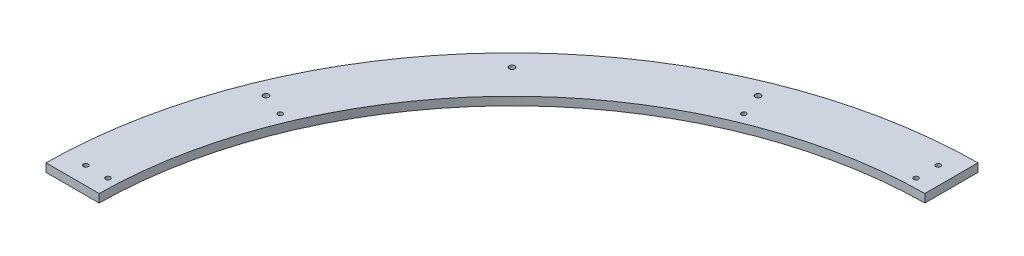
SolidWorks part; units mm, degrees
material "Pine"
ref_plane "Front Plane" through (0, 0, 0) normal (0, 0, 1) x (1, 0, 0)
ref_plane "Top Plane" through (0, 0, 0) normal (0, 1, 0) x (1, 0, 0)
ref_plane "Right Plane" through (0, 0, 0) normal (1, 0, 0) x (0, 0, -1)
sketch "Sketch1" plane through (0, 0, 0) normal (0, 1, 0) x (1, 0, 0)
  line L0 (-598.4875, 0) -> (-674.6875, 0)
  line L1 (598.4875, 0) -> (674.6875, 0)
  arc A0 (-598.4875, 0) -> (598.4875, 0) centre (0, 0) cw
  arc A1 (-674.6875, 0) -> (674.6875, 0) centre (0, 0) cw
  dimension "D2" = 598.4875
  dimension "D1" = 76.2
extrude "Boss-Extrude1" add sketch "Sketch1" along normal blind 11.9062
sketch "Sketch2" plane through (0, 11.9062, 0) normal (0, 1, 0) x (1, 0, 0)
  line L1 (-6.35, 598.4538) -> (6.35, 598.4538)
  line L2 (-6.35, 598.4538) -> (-6.35, 636.5875)
  line L3 (-6.35, 636.5875) -> (6.35, 636.5875)
  line L4 (6.35, 598.4538) -> (6.35, 636.5875)
  line L8 (598.4538, 6.35) -> (636.5875, 6.35)
  line L9 (0, 0) -> (0, 598.4538) construction
  line L14 (0, 674.6875) -> (0, 598.4875) construction
  line L15 (598.4538, 6.35) -> (598.4538, -6.35)
  line L16 (598.4538, -6.35) -> (636.5875, -6.35)
  line L17 (636.5875, 6.35) -> (636.5875, -6.35)
  line L18 (6.35, -598.4538) -> (6.35, -636.5875)
  line L19 (6.35, -598.4538) -> (-6.35, -598.4538)
  line L20 (-6.35, -598.4538) -> (-6.35, -636.5875)
  line L21 (6.35, -636.5875) -> (-6.35, -636.5875)
  line L22 (-598.4538, -6.35) -> (-636.5875, -6.35)
  line L23 (-598.4538, -6.35) -> (-598.4538, 6.35)
  line L24 (-598.4538, 6.35) -> (-636.5875, 6.35)
  line L25 (-636.5875, -6.35) -> (-636.5875, 6.35)
  line L26 (598.4875, 0) -> (674.6875, 0) construction
  arc A0 (598.4875, 0) -> (-598.4875, 0) centre (0, 0) ccw construction
  arc A1 (674.6875, 0) -> (-674.6875, 0) centre (0, 0) ccw construction
  point P7 (0, 598.4538)
  point P16 (0, 0)
  point P23 (0, 636.5875)
  point P33 (0, 0)
  dimension "D1" = 38.1
  dimension "D2" = 12.7
  dimension "D3" = 4
extrude "Cut-Extrude1" cut sketch "Sketch2" against normal through all
hole_wizard "1/4 Clearance Hole2" positions "Sketch6" profile "Sketch7" hole size "1/4" standard "ANSI Inch" end condition through all
sketch "Sketch6" plane through (0, 11.9062, 0) normal (0, 1, 0) x (1, 0, 0)
  line L0 (0, 636.5875) -> (0, 598.4875) construction
  line L1 (6.35, 636.5875) -> (-6.35, 636.5875) construction
  line L2 (-6.35, 636.5875) -> (-6.35, 598.4538) construction
  line L3 (-636.5875, 0) -> (-598.4875, 0) construction
  line L4 (-31.75, 642.9375) -> (-31.75, 611.1875) construction
  line L5 (-31.75, 611.1875) -> (-31.75, 598.4875) construction
  line L6 (-31.75, 598.4875) -> (0, 598.4875) construction
  line L8 (-598.4875, 0) -> (-598.4875, 31.75) construction
  line L9 (-598.4875, 31.75) -> (-611.1875, 31.75) construction
  line L10 (-611.1875, 31.75) -> (-642.9375, 31.75) construction
  line L11 (-598.4875, 0) -> (-552.9304, 229.0313) construction
  line L12 (-552.9304, 229.0313) -> (-423.1946, 423.1946) construction
  line L13 (-423.1946, 423.1946) -> (0, 0) construction
  line L15 (-552.9304, 229.0313) -> (-567.5969, 235.1064) construction
  arc A0 (-6.35, 598.4538) -> (-598.4538, 6.35) centre (0, 0) ccw construction
  point P0 (-31.75, 642.9375)
  point P2 (-31.75, 611.1875)
  point P39 (-611.1875, 31.75)
  point P42 (-642.9375, 31.75)
  point P62 (-567.5969, 235.1064)
  point P70 (-235.1064, 567.5969)
  dimension "D1" = 38.1
  dimension "D2" = 25.4
  dimension "D3" = 12.7
  dimension "D4" = 31.75
  dimension "D5" = 15.875
sketch "Sketch7" plane through (-31.75, 11.9062, -642.9375) normal (1, 0, 0) x (0, 0, 1)
  line L0 (0, 0) -> (0, 11.9062)
  line L1 (0, 11.9062) -> (3.3782, 11.9062)
  line L2 (3.3782, 11.9062) -> (3.3782, 0)
  line L5 (3.3782, 0) -> (0, 0)
  line L11 (0, -6.35) -> (0, 107.95) construction
  dimension "Thru Hole Dia." = 6.7564
  dimension "Thru Hole Depth" = 11.9062
sketch "Sketch8" plane through (0, 11.9062, 0) normal (0, 1, 0) x (1, 0, 0)
  line L1 (674.6875, 0) -> (0, 0)
  line L2 (674.6875, 0) -> (674.6875, 674.6875)
  line L3 (674.6875, 674.6875) -> (0, 674.6875)
  line L4 (0, 0) -> (0, 674.6875)
  arc A0 (674.6875, 0) -> (-674.6875, 0) centre (0, 0) ccw construction
extrude "Cut-Extrude4" cut sketch "Sketch8" against normal through all
hole_wizard "5/16 (0.3125) Diameter Hole1" positions "Sketch11" profile "Sketch12" hole size "5/16" standard "ANSI Inch" end condition through all
sketch "Sketch11" plane through (0, 11.9062, 0) normal (0, 1, 0) x (1, 0, 0)
  line L0 (0, 0) -> (-478.1986, 478.1986) construction
  line L1 (-625.2272, 257.7573) -> (0, 0) construction
  line L3 (-478.1986, 478.1986) -> (-479.3212, 479.3212) construction
  line L5 (-479.3212, 479.3212) -> (-480.6628, 480.6628) construction
  arc A1 (0, 674.6875) -> (-674.6875, 0) centre (0, 0) ccw construction
  arc A2 (-478.1986, 478.1986) -> (-625.2272, 257.7573) centre (0, 0) ccw construction
  arc A3 (-459.1156, 459.1156) -> (-600.2768, 247.4712) centre (0, 0) ccw construction
  point P12 (-477.0761, 477.0761)
  point P16 (-459.1156, 459.1156)
  point P18 (-600.2768, 247.4712)
  point P46 (-247.4712, 600.2768)
  dimension "D2" = 266.7
  dimension "D1" = 1.5875
  dimension "D3" = 1.5875
  dimension "D4" = 1.8974
  dimension "D5" = 30.4724
  dimension "D6" = 25.4
sketch "Sketch12" plane through (-247.4712, 11.9062, -600.2768) normal (1, 0, 0) x (0, 0, 1)
  line L0 (0, 0) -> (0, 11.9062)
  line L1 (0, 11.9062) -> (3.9687, 11.9062)
  line L2 (3.9687, 11.9062) -> (3.9687, 0)
  line L5 (3.9687, 0) -> (0, 0)
  line L11 (0, -6.35) -> (0, 107.95) construction
  dimension "Thru Hole Dia." = 7.9375
  dimension "Thru Hole Depth" = 11.9062
sketch "Sketch14" plane through (0, 11.9062, 0) normal (0, 1, 0) x (1, 0, 0)
  line L1 (-6.35, 598.4538) -> (0, 598.4538)
  line L2 (-6.35, 598.4538) -> (-6.35, 674.6875)
  line L3 (-6.35, 674.6875) -> (0, 674.6875)
  line L4 (0, 598.4538) -> (0, 674.6875)
  line L5 (-598.4538, 6.35) -> (-674.6875, 6.35)
  line L6 (-598.4538, 6.35) -> (-598.4538, 0)
  line L7 (-598.4538, 0) -> (-674.6875, 0)
  line L8 (-674.6875, 6.35) -> (-674.6875, 0)
extrude "Cut-Extrude7" cut sketch "Sketch14" against normal through all
ref_plane "Plane1" through (-302.4019, 0, -302.4019) normal (-0.7071, 0, -0.7071) x (-0.7071, 0, 0.7071)
ref_plane "Plane2" through (-477.0761, 0, -477.0761) normal (-0.7071, 0, -0.7071) x (-0.7071, 0, 0.7071)
ref_plane "Plane3" through (0, 0, 0) normal (-0.7071, 0, 0.7071) x (0.7071, 0, 0.7071)
ref_plane "Plane4" through (-334.1538, 0, 334.1538) normal (-0.7071, 0, 0.7071) x (0.7071, 0, 0.7071)
